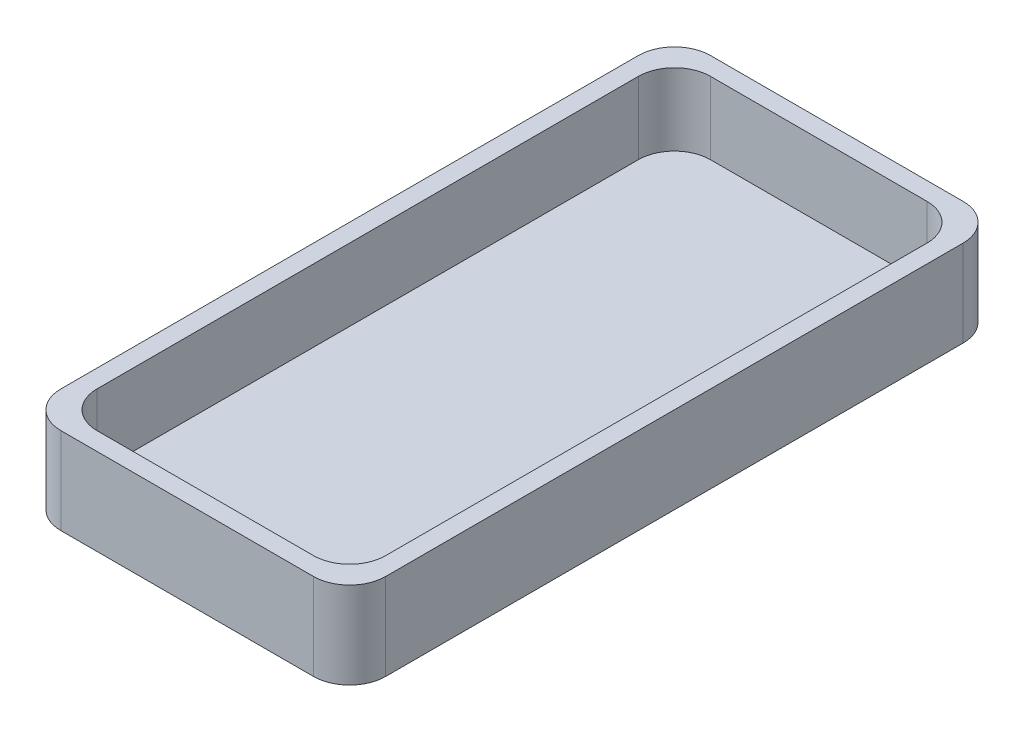
SolidWorks part; units mm, degrees
ref_plane "Front Plane" through (0, 0, 0) normal (0, 0, 1) x (1, 0, 0)
ref_plane "Top Plane" through (0, 0, 0) normal (0, 1, 0) x (1, 0, 0)
ref_plane "Right Plane" through (0, 0, 0) normal (1, 0, 0) x (0, 0, -1)
sketch "Sketch3" plane through (0, 0, 0) normal (0, 1, 0) x (1, 0, 0)
  line L0 (-45, 0) -> (45, 0) construction
  line L1 (-45, 90) -> (-45, -90) construction
  line L2 (-45, 80) -> (-45, -80)
  line L3 (-35, -90) -> (35, -90)
  line L4 (45, -80) -> (45, 80)
  line L5 (35, 90) -> (-35, 90)
  arc A0 (35, -90) -> (45, -80) centre (35, -80) ccw
  arc A1 (-45, -80) -> (-35, -90) centre (-35, -80) ccw
  arc A2 (45, 80) -> (35, 90) centre (35, 80) ccw
  arc A3 (-45, 80) -> (-35, 90) centre (-35, 80) cw
  point P4 (0, 0)
  point P7 (-45, 0)
  dimension "D3" = 10
  dimension "D1" = 90
  dimension "D2" = 180
extrude "Boss-Extrude1" add sketch "Sketch3" along normal blind 24
sketch "Sketch4" plane through (0, 24, 0) normal (0, 1, 0) x (1, 0, 0)
  line L0 (-40, 0) -> (40, 0) construction
  line L1 (-40, 85) -> (-40, -85) construction
  line L2 (-40, 75) -> (-40, -75)
  line L3 (-30, -85) -> (30, -85)
  line L4 (40, -75) -> (40, 75)
  line L5 (30, 85) -> (-30, 85)
  arc A0 (30, -85) -> (40, -75) centre (30, -75) ccw
  arc A1 (-40, -75) -> (-30, -85) centre (-30, -75) ccw
  arc A2 (40, 75) -> (30, 85) centre (30, 75) ccw
  arc A3 (-40, 75) -> (-30, 85) centre (-30, 75) cw
  point P4 (0, 0)
  point P8 (-40, 0)
  dimension "D3" = 10
  dimension "D1" = 80
  dimension "D2" = 170
extrude "Cut-Extrude1" cut sketch "Sketch4" against normal blind 20
sketch "Sketch6" plane through (0, 0, 85) normal (0, 0, -1) x (-1, 0, 0)
  line L0 (0, 0) -> (0, 44.6125) construction
sketch "Sketch7" plane through (0, 0, 85) normal (0, 0, -1) x (-1, 0, 0)
  line L0 (-35, 4.0334) -> (35, 4.0334)
  line L2 (35, 24) -> (35, 0) construction
  point P3 (0, 4.0334)
